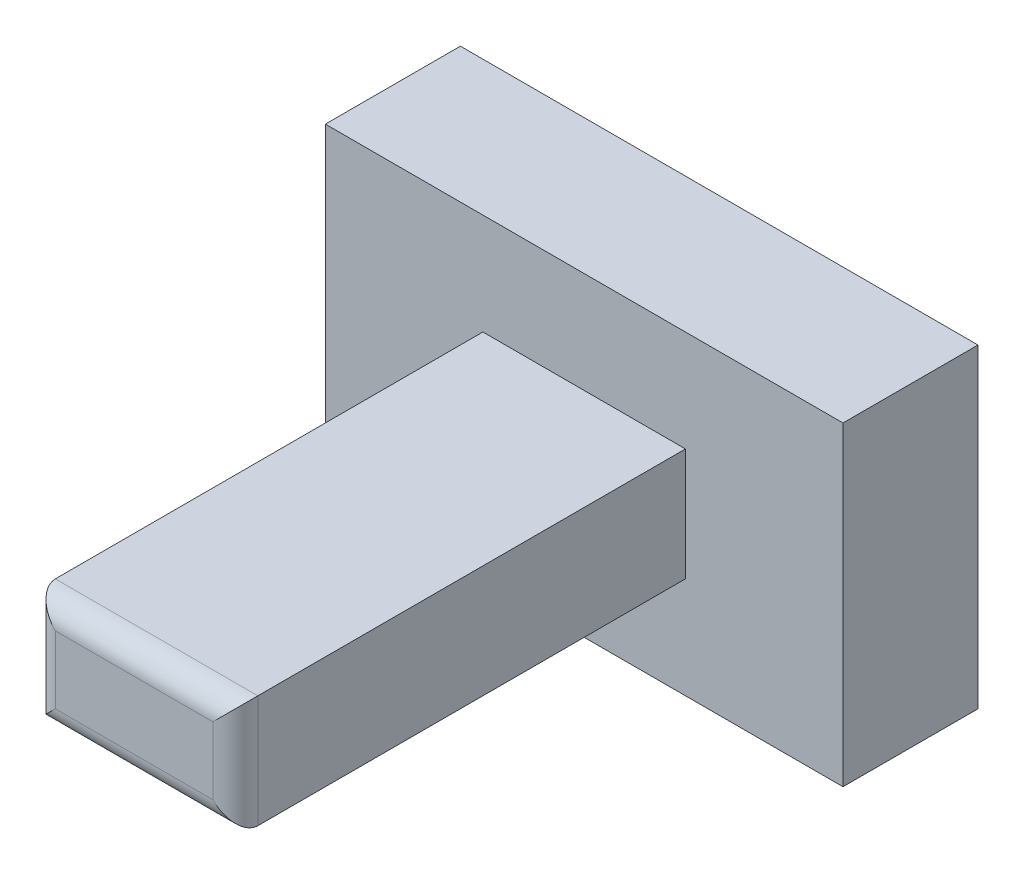
SolidWorks part; units mm, degrees
ref_plane "Ebene vorne" through (0, 0, 0) normal (0, 0, 1) x (1, 0, 0)
ref_plane "Ebene oben" through (0, 0, 0) normal (0, 1, 0) x (1, 0, 0)
ref_plane "Ebene rechts" through (0, 0, 0) normal (1, 0, 0) x (0, 0, -1)
sketch "Skizze1" plane through (0, 0, 0) normal (0, 0, 1) x (1, 0, 0)
  line L1 (-0.9, -0.5) -> (0.9, -0.5)
  line L2 (-0.9, -0.5) -> (-0.9, 0.5)
  line L3 (-0.9, 0.5) -> (0.9, 0.5)
  line L4 (0.9, -0.5) -> (0.9, 0.5)
  line L5 (-0.9, -0.5) -> (0.9, 0.5) construction
  line L6 (-0.9, 0.5) -> (0.9, -0.5) construction
  point P0 (0, 0)
  dimension "D1" = 1
  dimension "D2" = 1.8
extrude "Aufsatz-Linear austragen1" add sketch "Skizze1" along normal blind 4
sketch "Skizze2" plane through (0, 0, 0) normal (0, 0, -1) x (-1, 0, 0)
  line L1 (-2.3, -1.4) -> (2.3, -1.4)
  line L2 (-2.3, -1.4) -> (-2.3, 1.4)
  line L3 (-2.3, 1.4) -> (2.3, 1.4)
  line L4 (2.3, -1.4) -> (2.3, 1.4)
  line L5 (-2.3, -1.4) -> (2.3, 1.4) construction
  line L6 (-2.3, 1.4) -> (2.3, -1.4) construction
  point P0 (0, 0)
  dimension "D1" = 4.6
  dimension "D2" = 2.8
extrude "Aufsatz-Linear austragen2" add sketch "Skizze2" along normal blind 1.2
fillet "Verrundung1" radius 0.2 4 edges at (-0.9, 0, 4) (0, -0.5, 4) (0.9, 0, 4) (0, 0.5, 4)
